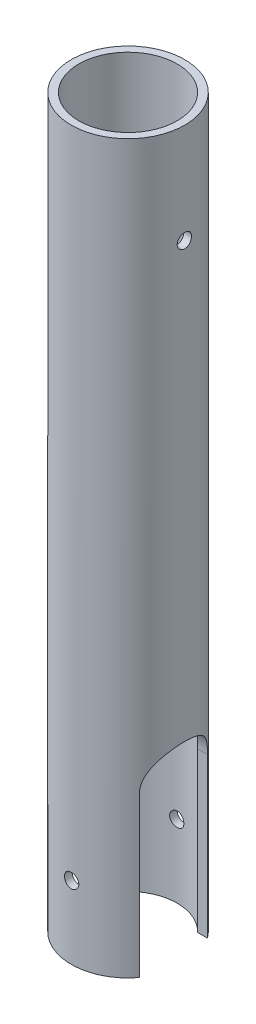
SolidWorks part; units mm, degrees
ref_plane "Front Plane" through (0, 0, 0) normal (0, 0, 1) x (1, 0, 0)
ref_plane "Top Plane" through (0, 0, 0) normal (0, 1, 0) x (1, 0, 0)
ref_plane "Right Plane" through (0, 0, 0) normal (1, 0, 0) x (0, 0, -1)
sketch "Sketch1" plane through (0, 0, 0) normal (0, 1, 0) x (1, 0, 0)
  circle A0 centre (0, 0) radius 15.875
  circle A1 centre (0, 0) radius 13.7668
  dimension "D1" = 31.75
  dimension "D2" = 2.1082
extrude "Boss-Extrude1" add sketch "Sketch1" along normal blind 203.2 contours A0 | A1
sketch "Sketch3" plane through (0, 0, 0) normal (1, 0, 0) x (0, 0, -1)
  line L1 (0, 203.2) -> (0, 180.5053) construction
  line L8 (15.875, 203.2) -> (-15.875, 203.2) construction
  circle A4 centre (0, 175.26) radius 2
  dimension "D1" = 27.94
  dimension "D2" = 4
sketch "Sketch4" plane through (0, 0, 0) normal (0, 0, 1) x (1, 0, 0)
  line L0 (-15.875, 0) -> (15.875, 0) construction
  circle A0 centre (0, 20.32) radius 2
  dimension "D1" = 4
  dimension "D2" = 20.32
extrude "Cut-Extrude2" cut sketch "Sketch4" against normal through all both and the other way through all contours A0
extrude "Cut-Extrude3" cut sketch "Sketch3" against normal through all both and the other way through all
sketch "Sketch5" plane through (0, 0, 0) normal (1, 0, 0) x (0, 0, -1)
  line L0 (0, 0) -> (0, 162.4793) construction
  line L1 (5.8133, 20.32) -> (-6.8101, 20.32) construction
  line L2 (-15.875, 0) -> (15.875, 0) construction
  line L9 (9.525, 44.45) -> (9.525, 0)
  line L10 (9.525, 0) -> (-9.525, 0)
  line L11 (-9.525, 44.45) -> (-9.525, 0)
  line L12 (9.525, 44.45) -> (-9.525, 0) construction
  line L13 (9.525, 0) -> (-9.525, 44.45) construction
  arc A0 (9.525, 44.45) -> (-9.525, 44.45) centre (0, 44.45) ccw
  point P7 (0, 22.225)
  point P8 (0, 22.225)
  dimension "D4" = 9.525
  dimension "D1" = 20.32
  dimension "D2" = 19.05
  dimension "D3" = 44.45
extrude "Cut-Extrude4" cut sketch "Sketch5" along normal through all
sketch "Sketch6" plane through (0, 0, 0) normal (1, 0, 0) x (0, 0, -1)
  line L0 (0, 0) -> (0, 116.6678) construction
  line L1 (-15.875, 0) -> (15.875, 0) construction
  line L2 (-9.525, 0) -> (9.525, 0)
  line L3 (-9.525, 0) -> (-9.525, 12.7)
  line L5 (9.525, 0) -> (9.525, 12.7)
  line L6 (-9.525, 0) -> (9.525, 12.7) construction
  line L7 (-9.525, 12.7) -> (9.525, 0) construction
  arc A0 (9.525, 12.7) -> (-9.525, 12.7) centre (0, 12.7) ccw
  arc A1 (9.525, 12.7) -> (-9.525, 12.7) centre (0, 12.7) ccw
  point P3 (0, 6.35)
  dimension "D1" = 19.05
  dimension "D2" = 12.7
extrude "Cut-Extrude5" cut sketch "Sketch6" against normal through all contours A0 L3 L2 L5
